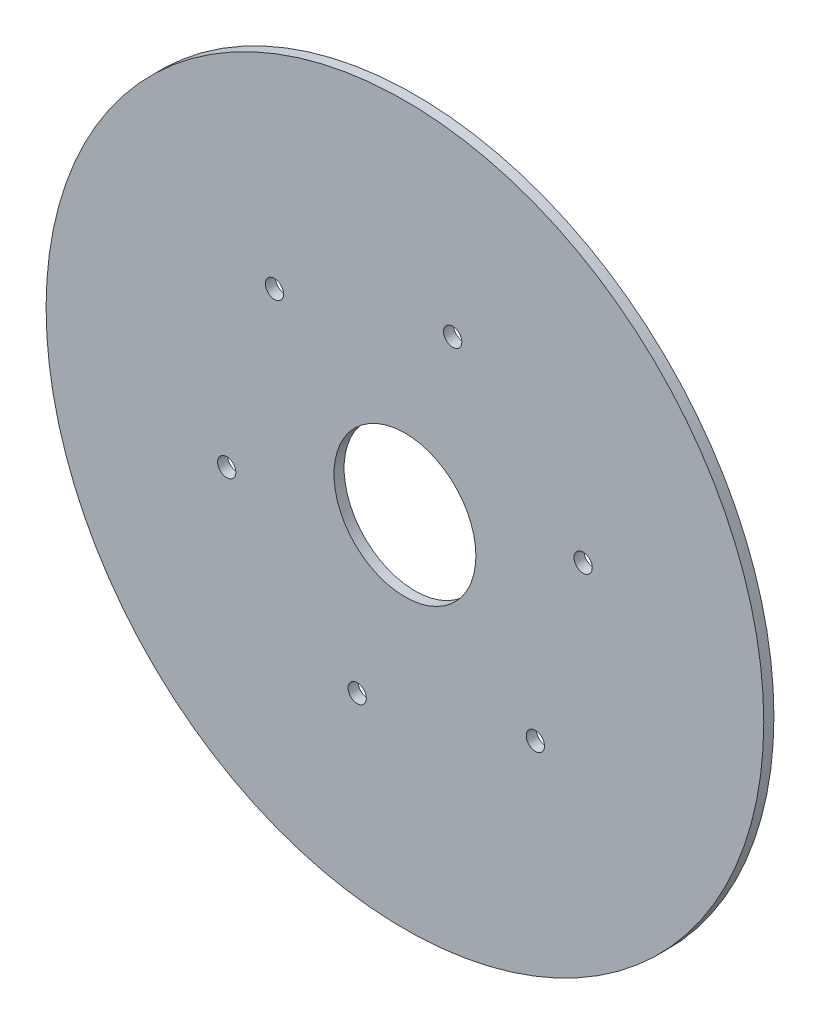
SolidWorks part; units mm, degrees
ref_plane "Спереди" through (0, 0, 0) normal (0, 0, 1) x (1, 0, 0)
ref_plane "Сверху" through (0, 0, 0) normal (0, 1, 0) x (1, 0, 0)
ref_plane "Справа" through (0, 0, 0) normal (1, 0, 0) x (0, 0, -1)
sketch "Эскиз1" plane through (0, 0, 0) normal (0, 0, 1) x (1, 0, 0)
  circle A0 centre (0, 0) radius 88.5
  circle A1 centre (0, 0) radius 17.5
extrude "Front_cover_reference" add sketch "Эскиз1" along normal blind 2.5 from offset 47.5
sketch "Эскиз2" plane through (0, 0, 0) normal (0, 0, 1) x (1, 0, 0)
  circle A0 centre (43.9496, 11.7763) radius 2.25
  circle A1 centre (11.7763, 43.9496) radius 2.25
  circle A2 centre (-32.1734, 32.1734) radius 2.25
  circle A3 centre (-43.9496, -11.7763) radius 2.25
  circle A4 centre (-11.7763, -43.9496) radius 2.25
  circle A5 centre (32.1734, -32.1734) radius 2.25
extrude "Through_holes" cut sketch "Эскиз2" against normal mid plane 200
